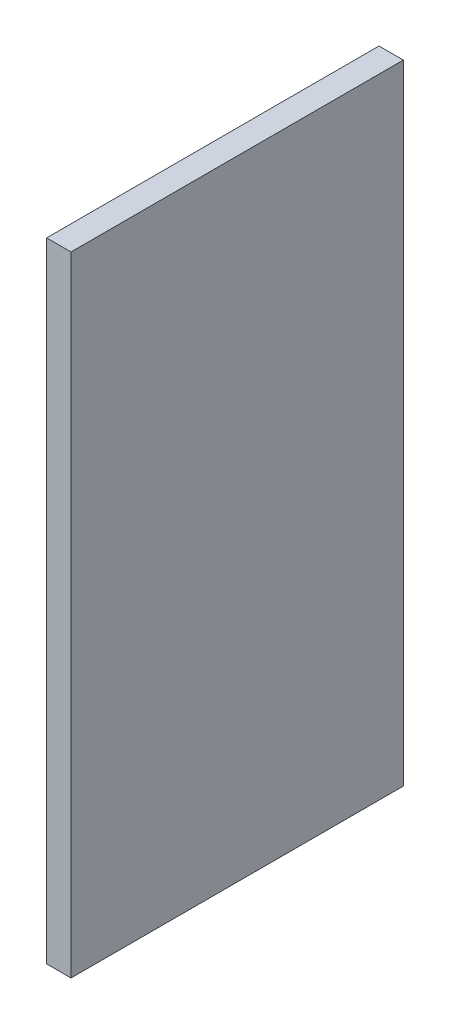
SolidWorks part; units mm, degrees
ref_plane "Front Plane" through (0, 0, 0) normal (0, 0, 1) x (1, 0, 0)
ref_plane "Top Plane" through (0, 0, 0) normal (0, 1, 0) x (1, 0, 0)
ref_plane "Right Plane" through (0, 0, 0) normal (1, 0, 0) x (0, 0, -1)
other "Configuration Table"
sketch "Sketch1" plane through (0, 0, 0) normal (0, 0, 1) x (1, 0, 0)
  line L1 (1338.5, 121.5) -> (1398.5, 121.5)
  line L2 (1338.5, 121.5) -> (1338.5, 1670)
  line L3 (1338.5, 1670) -> (1398.5, 1670)
  line L4 (1398.5, 121.5) -> (1398.5, 1670)
extrude "STORE_pu_yan_sag_1" add sketch "Sketch1" against normal blind 818.5 separate body
